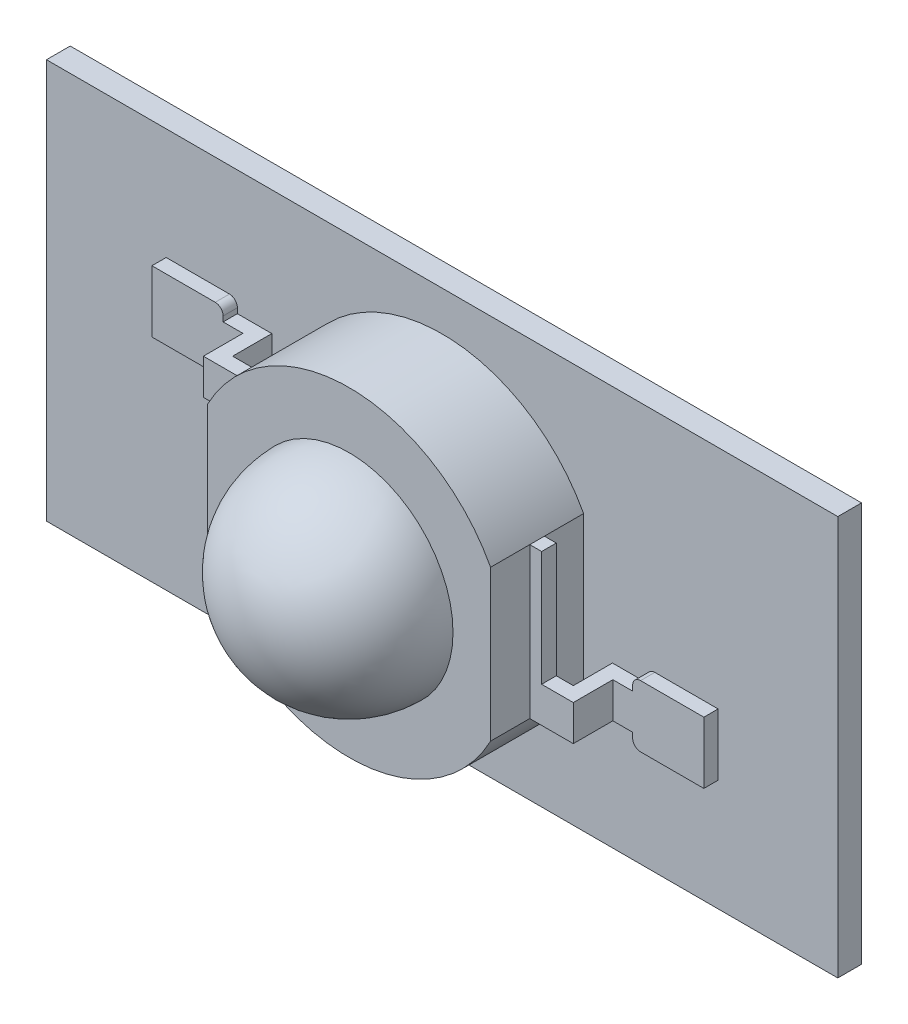
SolidWorks part; units mm, degrees
ref_plane "Front Plane" through (0, 0, 0) normal (0, 0, 1) x (1, 0, 0)
ref_plane "Top Plane" through (0, 0, 0) normal (0, 1, 0) x (1, 0, 0)
ref_plane "Right Plane" through (0, 0, 0) normal (1, 0, 0) x (0, 0, -1)
sketch "Sketch1" plane through (0, 0, 0) normal (0, 0, 1) x (1, 0, 0)
  line L0 (0, 0) -> (0, 4.05) construction
  circle A0 centre (0, 4.05) radius 4.05
  dimension "D1" = 4.05
extrude "Boss-Extrude1" add sketch "Sketch1" along normal blind 2.35
sketch "Sketch2" plane through (0, 0, 2.35) normal (0, 0, 1) x (1, 0, 0)
  line L0 (0, 0) -> (0, 8.1) construction
  line L2 (-0.5, 3.55) -> (0.5, 3.55)
  line L3 (-0.5, 3.55) -> (-0.5, 4.55)
  line L4 (-0.5, 4.55) -> (0.5, 4.55)
  line L5 (0.5, 3.55) -> (0.5, 4.55)
  line L6 (-0.5, 3.55) -> (0.5, 4.55) construction
  line L7 (-0.5, 4.55) -> (0.5, 3.55) construction
  circle A0 centre (0, 4.05) radius 4.05 construction
  circle A1 centre (0, 4.05) radius 1.5
  dimension "D1" = 3
  dimension "D2" = 1
  dimension "D3" = 1
extrude "Boss-Extrude2" add sketch "Sketch2" along normal blind 0.2
sketch "Sketch3" plane through (0, 0, 2.35) normal (0, 0, 1) x (1, 0, 0)
  line L0 (0, 4.05) -> (-4.05, 4.05) construction
  line L1 (0, 4.05) -> (4.05, 4.05) construction
  line L2 (-2.625, 4.05) -> (-2.5, 4.05)
  line L3 (2.625, 4.05) -> (2.5, 4.05)
  arc A0 (2.625, 4.05) -> (-2.625, 4.05) centre (0, 4.05) ccw
  circle A1 centre (0, 4.05) radius 4.05 construction
  arc A2 (2.5, 4.05) -> (-2.5, 4.05) centre (0, 4.05) ccw
  dimension "D1" = 2.625
  dimension "D2" = 2.5
revolve "Revolve1" add sketch "Sketch3" angle 180 about L1
sketch "Sketch4" plane through (0, 0, 2.35) normal (0, 0, 1) x (1, 0, 0)
  line L0 (-4.05, 4.05) -> (4.05, 4.05) construction
  line L1 (0, 0) -> (0, 8.1) construction
  line L2 (-3.575, 0) -> (-4.05, 0)
  line L3 (-3.575, 0) -> (-3.575, 8.1)
  line L4 (-3.575, 8.1) -> (-4.05, 8.1)
  line L5 (-4.05, 0) -> (-4.05, 8.1)
  line L6 (3.575, 8.1) -> (4.05, 8.1)
  line L7 (4.05, 0) -> (4.05, 8.1)
  line L8 (3.575, 0) -> (4.05, 0)
  line L9 (3.575, 0) -> (3.575, 8.1)
  circle A0 centre (0, 4.05) radius 4.05 construction
  point P9 (0, 4.05)
  dimension "D1" = 3.575
  dimension "D2" = 0.475
  dimension "D3" = 4.05
  dimension "D4" = 4.05
extrude "Cut-Extrude1" cut sketch "Sketch4" against normal through all
sketch "Sketch5" plane through (-3.575, 0, 0) normal (-1, 0, 0) x (0, 0, 1)
  line L0 (0, 4.05) -> (2.35, 4.05) construction
  line L1 (0, 2.1469) -> (0, 5.9531) construction
  line L2 (2.35, 2.1469) -> (2.35, 5.9531) construction
  line L3 (0, 5.9531) -> (2.35, 5.9531) construction
  line L4 (1.36, 2.1469) -> (0.99, 2.1469)
  line L5 (1.36, 2.1469) -> (1.36, 5.9531)
  line L6 (1.36, 5.9531) -> (0.99, 5.9531)
  line L7 (0.99, 2.1469) -> (0.99, 5.9531)
  line L8 (1.36, 2.1469) -> (0.99, 5.9531) construction
  line L9 (1.36, 5.9531) -> (0.99, 2.1469) construction
  point P6 (1.175, 4.05)
  dimension "D1" = 0.37
extrude "Boss-Extrude3" add sketch "Sketch5" along normal blind 0.3
sketch "Sketch6" plane through (-3.875, 0, 0) normal (-1, 0, 0) x (0, 0, 1)
  line L0 (1.36, 2.1469) -> (1.36, 5.9531) construction
  line L1 (0.99, 5.9531) -> (1.36, 5.9531)
  line L2 (0.99, 5.9531) -> (0.99, 5.0531)
  line L3 (0.99, 5.0531) -> (1.36, 5.0531)
  line L4 (1.36, 5.9531) -> (1.36, 5.0531)
  dimension "D1" = 0.9
extrude "Boss-Extrude4" add sketch "Sketch6" along normal blind 0.8
sketch "Sketch7" plane through (0, 0, 0.99) normal (0, 0, -1) x (-1, 0, 0)
  line L0 (4.675, 5.0531) -> (3.875, 5.0531) construction
  line L1 (4.675, 5.9531) -> (4.305, 5.9531)
  line L2 (4.675, 5.9531) -> (4.675, 5.0531)
  line L3 (4.675, 5.0531) -> (4.305, 5.0531)
  line L4 (4.305, 5.9531) -> (4.305, 5.0531)
  dimension "D1" = 0.37
extrude "Boss-Extrude5" add sketch "Sketch7" along normal blind 1
sketch "Sketch8" plane through (0, 0, -0.01) normal (0, 0, -1) x (-1, 0, 0)
  line L0 (5.175, 5.5031) -> (6.975, 5.5031) construction
  line L1 (4.675, 5.9531) -> (5.175, 5.9531)
  line L2 (4.675, 5.9531) -> (4.675, 5.0531)
  line L3 (4.675, 5.0531) -> (5.175, 5.0531)
  line L4 (5.175, 5.9531) -> (5.175, 5.0531)
  line L5 (5.375, 6.2831) -> (6.975, 6.2831)
  line L6 (5.175, 5.5031) -> (6.975, 5.5031)
  line L7 (5.175, 6.0831) -> (5.175, 4.9231)
  line L8 (5.375, 4.7231) -> (6.975, 4.7231)
  line L9 (6.975, 6.2831) -> (6.975, 4.7231)
  arc A0 (5.175, 4.9231) -> (5.375, 4.7231) centre (5.375, 4.9231) ccw
  arc A1 (5.375, 6.2831) -> (5.175, 6.0831) centre (5.375, 6.0831) ccw
  point P13 (5.175, 4.7231)
  point P16 (5.175, 6.2831)
  line M11 (4.675, 5.0531) -> (4.675, 5.9531)
  dimension "D5" = 0.2
  dimension "D1" = 0.5
  dimension "D2" = 0.9
  dimension "D3" = 1.8
  dimension "D4" = 0.78
extrude "Boss-Extrude6" add sketch "Sketch8" against normal blind 0.37 contours L5 A1 L7 L4 L6 L9 | L7 A0 L8 L9 L6 L4 | L4 L1 L3 M11
sketch "Sketch9" plane through (3.575, 0, 0) normal (1, 0, 0) x (0, 0, -1)
  line L0 (-2.35, 4.05) -> (0, 4.05) construction
  line L1 (-2.35, 5.9531) -> (-2.35, 2.1469) construction
  line L2 (0, 5.9531) -> (0, 2.1469) construction
  line L3 (-2.35, 5.9531) -> (0, 5.9531) construction
  line L4 (-0.99, 2.1469) -> (-1.36, 2.1469)
  line L5 (-0.99, 2.1469) -> (-0.99, 5.9531)
  line L6 (-0.99, 5.9531) -> (-1.36, 5.9531)
  line L7 (-1.36, 2.1469) -> (-1.36, 5.9531)
  line L8 (-0.99, 2.1469) -> (-1.36, 5.9531) construction
  line L9 (-0.99, 5.9531) -> (-1.36, 2.1469) construction
  point P6 (-1.175, 4.05)
  dimension "D1" = 0.37
extrude "Boss-Extrude7" add sketch "Sketch9" along normal blind 0.3
sketch "Sketch10" plane through (3.875, 0, 0) normal (1, 0, 0) x (0, 0, -1)
  line L0 (-1.36, 5.9531) -> (-1.36, 2.1469) construction
  line L1 (-0.99, 2.1469) -> (-1.36, 2.1469)
  line L2 (-0.99, 2.1469) -> (-0.99, 3.0469)
  line L3 (-0.99, 3.0469) -> (-1.36, 3.0469)
  line L4 (-1.36, 2.1469) -> (-1.36, 3.0469)
  dimension "D1" = 0.9
extrude "Boss-Extrude8" add sketch "Sketch10" along normal blind 0.8
sketch "Sketch11" plane through (0, 0, 0.99) normal (0, 0, -1) x (-1, 0, 0)
  line L0 (-4.675, 3.0469) -> (-3.875, 3.0469) construction
  line L1 (-4.675, 2.1469) -> (-4.305, 2.1469)
  line L2 (-4.675, 2.1469) -> (-4.675, 3.0469)
  line L3 (-4.675, 3.0469) -> (-4.305, 3.0469)
  line L4 (-4.305, 2.1469) -> (-4.305, 3.0469)
  dimension "D1" = 0.37
extrude "Boss-Extrude9" add sketch "Sketch11" along normal blind 1
sketch "Sketch12" plane through (0, 0, -0.01) normal (0, 0, -1) x (-1, 0, 0)
  line L0 (-5.175, 2.5969) -> (-6.975, 2.5969) construction
  line L1 (-4.675, 2.1469) -> (-5.175, 2.1469)
  line L2 (-4.675, 2.1469) -> (-4.675, 3.0469)
  line L3 (-4.675, 3.0469) -> (-5.175, 3.0469)
  line L4 (-5.175, 2.1469) -> (-5.175, 3.0469)
  line L5 (-5.375, 3.3769) -> (-6.975, 3.3769)
  line L6 (-5.175, 2.5969) -> (-6.975, 2.5969)
  line L7 (-5.175, 3.1769) -> (-5.175, 2.0169)
  line L8 (-5.375, 1.8169) -> (-6.975, 1.8169)
  line L9 (-6.975, 3.3769) -> (-6.975, 1.8169)
  arc A0 (-5.375, 3.3769) -> (-5.175, 3.1769) centre (-5.375, 3.1769) cw
  arc A1 (-5.175, 2.0169) -> (-5.375, 1.8169) centre (-5.375, 2.0169) cw
  point P13 (-5.175, 3.3769)
  point P16 (-5.175, 1.8169)
  line M5 (-4.675, 3.0469) -> (-4.675, 2.1469)
  dimension "D5" = 0.2
  dimension "D1" = 0.5
  dimension "D2" = 0.9
  dimension "D3" = 1.8
  dimension "D4" = 0.78
extrude "Boss-Extrude10" add sketch "Sketch12" against normal blind 0.37 contours L4 L1 L3 M5 | A1 L7 L4 L6 L9 L8 | A0 L5 L9 L6 L4 L7
sketch "Sketch13" plane through (0, 0, 0) normal (0, 0, -1) x (-1, 0, 0)
  line L0 (0, 0) -> (0, 8.1) construction
  arc A0 (3.575, 5.9531) -> (-3.575, 5.9531) centre (0, 4.05) ccw construction
  circle A1 centre (0, 4.05) radius 2.75
  dimension "D1" = 5.5
extrude "Boss-Extrude11" add sketch "Sketch13" along normal blind 0.1
sketch "Sketch14" plane through (0, 0, 0) normal (0, 0, -1) x (-1, 0, 0)
  line L0 (0, 0) -> (0, -1) construction
  line L1 (0, -1) -> (10, -1) construction
  line L2 (0, -1) -> (-10, -1) construction
  line L12 (10, -1) -> (-10, -1)
  line L13 (10, -1) -> (10, 9.1)
  line L14 (10, 9.1) -> (-10, 9.1)
  line L15 (-10, -1) -> (-10, 9.1)
  arc A0 (3.575, 5.9531) -> (-3.575, 5.9531) centre (0, 4.05) ccw construction
  point P11 (0, 8.1)
  dimension "D1" = 1
  dimension "D2" = 10
  dimension "D3" = 10
  dimension "D4" = 1
extrude "Boss-Extrude13" add sketch "Sketch14" along normal blind 0.6
